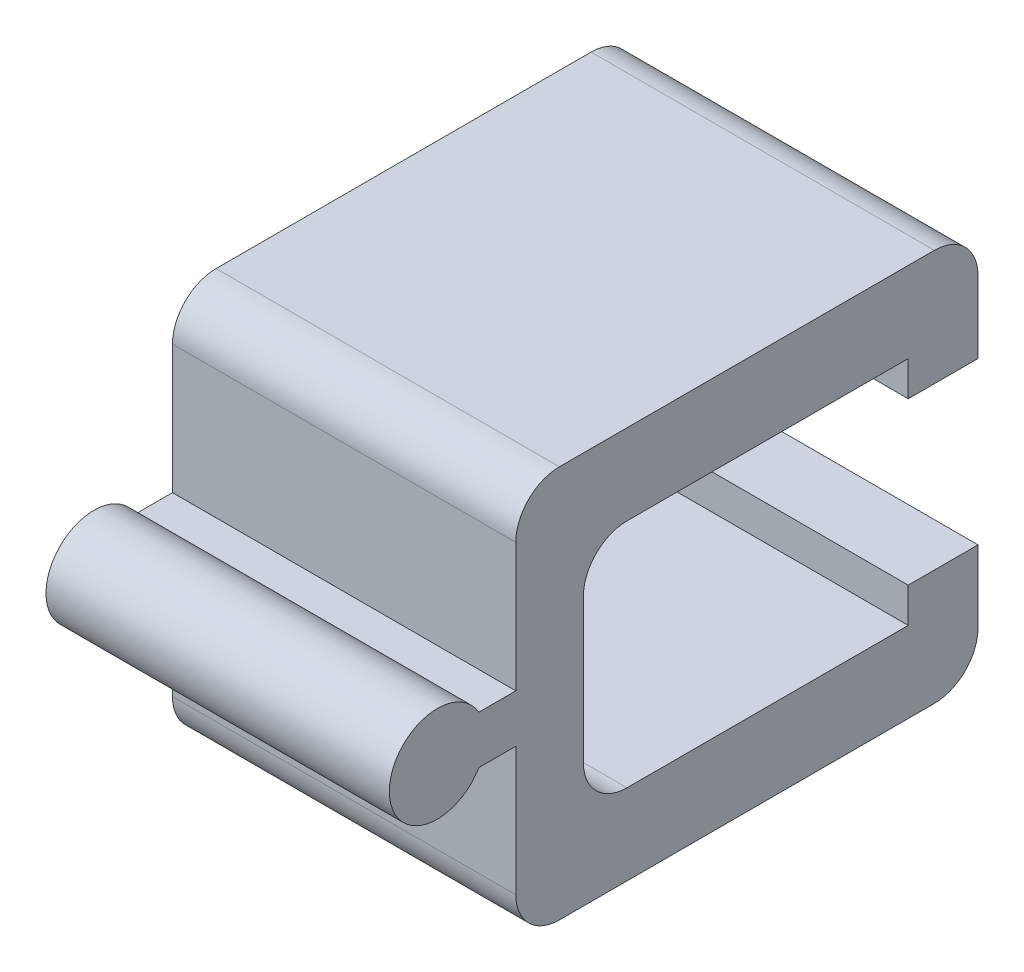
SolidWorks part; units mm, degrees
ref_plane "Front Plane" through (0, 0, 0) normal (0, 0, 1) x (1, 0, 0)
ref_plane "Top Plane" through (0, 0, 0) normal (0, 1, 0) x (1, 0, 0)
ref_plane "Right Plane" through (0, 0, 0) normal (1, 0, 0) x (0, 0, -1)
sketch "Sketch1" plane through (0, 0, 0) normal (1, 0, 0) x (0, 0, -1)
  line L5 (106.9183, 0.6042) -> (93.4563, 0.6042)
  line L11 (104.8863, -7.4603) -> (104.8863, -8.4763)
  line L15 (106.9183, 0.6042) -> (106.9183, -2.7613)
  line L16 (106.9183, -2.7613) -> (104.8863, -2.7613)
  line L17 (104.8863, -2.7613) -> (104.8863, -1.7453)
  line L18 (104.8863, -1.7453) -> (95.4248, -1.7453)
  line L19 (95.4248, -1.7453) -> (95.4248, -8.4763)
  line L20 (93.4563, 0.6042) -> (93.4563, -10.8258)
  line L21 (104.8863, -8.4763) -> (95.4248, -8.4763)
  line L23 (106.9183, -7.4603) -> (104.8863, -7.4603)
  line L25 (106.9183, -10.8258) -> (93.4563, -10.8258)
  line L26 (106.9183, -7.4603) -> (106.9183, -10.8258)
  point P16 (93.4563, -5.1108)
  point P17 (95.4248, -5.1108)
  dimension "D1" = 9.4615
  dimension "D2" = 6.731
  dimension "D3" = 1.016
  dimension "D4" = 2.032
  dimension "D5" = 13.462
  dimension "D6" = 11.43
  dimension "D7" = 1.016
  dimension "D8" = 13.462
extrude "MainBody" add sketch "Sketch1" along normal mid plane 10
sketch "Sketch4" plane through (0, -10.8258, 0) normal (0, -1, 0) x (1, 0, 0)
  line L4 (-5, -93.4563) -> (-5, -106.9183)
  line L5 (-5, -106.9183) -> (5, -106.9183)
  line L6 (5, -106.9183) -> (5, -93.4563)
  line L7 (5, -93.4563) -> (-5, -93.4563)
  line L8 (-5, -93.4563) -> (-5, -106.9183)
  line L9 (-5, -106.9183) -> (5, -106.9183)
  line L10 (5, -106.9183) -> (5, -93.4563)
  line L11 (5, -93.4563) -> (-5, -93.4563)
  dimension "D1" = 0
extrude "Boss-Extrude1" [suppressed] add sketch "Sketch4" along normal blind 6
hole_wizard "#6-32 Tapped Hole1" [suppressed] positions "Sketch2" profile "Sketch3" tap size "#6-32" standard "ANSI Inch"
sketch "Sketch2" [suppressed] plane through (0, 0, 6.0052) normal (0, 0, 1) x (1, 0, 0)
  line L2 (5, -14.1012) -> (-5, -14.1012) construction
  point P0 (0, -11.1012)
  point P12 (0, -14.1012)
  dimension "D1" = 3
sketch "Sketch3" plane through (0, -11.1012, 6.0052) normal (1, 0, 0) x (0, -1, 0)
  line L0 (0, 0) -> (0, 15.5)
  line L1 (0, 15.5) -> (1.7526, 15.5)
  line L2 (1.7526, 15.5) -> (1.7526, 0)
  line L5 (1.7526, 0) -> (0, 0)
  line L11 (0, -6.35) -> (0, 107.95) construction
  dimension "Thread Major Dia." = 3.5052
  dimension "Thru Tap Drill Depth" = 15.5
sketch "Sketch5" plane through (0, 0, -93.4563) normal (0, 0, 1) x (1, 0, 0)
  line L0 (5, 0.6042) -> (5, -10.8258) construction
  line L1 (-5, -10.8258) -> (5, -10.8258)
  line L2 (-5, -10.8258) -> (-5, 69.1742)
  line L3 (-5, 69.1742) -> (5, 69.1742)
  line L4 (5, -10.8258) -> (5, 69.1742)
  dimension "D1" = 80
extrude "HeightSupport" [suppressed] add sketch "Sketch5" along normal blind 4
fillet "Fillet2" [suppressed] radius 2
sketch "Sketch6" plane through (-5, 0, 0) normal (-1, 0, 0) x (0, 0, 1)
  line L0 (-93.5416, 72.7238) -> (-93.5416, 69.5488)
  line L2 (-93.5416, 69.3588) -> (-91.2556, 69.3588)
  line L6 (-93.5416, 67.8602) -> (-93.5416, 69.3588)
  line L7 (-93.5416, 69.3588) -> (-93.5416, 67.8602)
  line L8 (-93.5416, 67.8602) -> (-91.2556, 67.8602)
  line L9 (-91.2556, 69.3588) -> (-91.2556, 67.8602)
  line L14 (-106.9183, -2.7613) -> (-104.8863, -2.7613)
  line L15 (-104.8863, -2.7613) -> (-104.8863, -1.7453)
  line L16 (-104.8863, -1.7453) -> (-95.4248, -1.7453)
  line L17 (-95.4248, -1.7453) -> (-95.4248, -8.4763)
  line L18 (-95.4248, -8.4763) -> (-104.8863, -8.4763)
  line L19 (-104.8863, -8.4763) -> (-104.8863, -7.4603)
  line L20 (-104.8863, -7.4603) -> (-106.9183, -7.4603)
  line L21 (-106.9183, -7.4603) -> (-106.9183, -10.8258)
  line L22 (-106.9183, -10.8258) -> (-93.4563, -10.8258)
  line L23 (-93.4563, -10.8258) -> (-93.4563, 0.6042)
  line L26 (-93.4563, 0.6042) -> (-106.9183, 0.6042)
  line L27 (-106.9183, 0.6042) -> (-106.9183, -2.7613)
  line L28 (-106.9183, -2.7613) -> (-104.8863, -2.7613)
  line L29 (-104.8863, -2.7613) -> (-104.8863, -1.7453)
  line L30 (-104.8863, -1.7453) -> (-95.4248, -1.7453)
  line L31 (-95.4248, -1.7453) -> (-95.4248, -8.4763)
  line L32 (-95.4248, -8.4763) -> (-104.8863, -8.4763)
  line L34 (-104.8863, -7.4603) -> (-106.9183, -7.4603)
  line L35 (-106.9183, -7.4603) -> (-106.9183, -10.8258)
  line L36 (-106.9183, -10.8258) -> (-93.4563, -10.8258)
  line L40 (-93.4563, 0.6042) -> (-106.9183, 0.6042)
  line L41 (-106.9183, 0.6042) -> (-106.9183, -2.7613)
  line L48 (-104.8863, -8.4763) -> (-104.8863, -7.4603)
  line L49 (-93.4563, -10.8258) -> (-93.4563, 0.6042)
  circle A3 centre (-91.2556, 68.6095) radius 1.3843
  point P10 (-64.013, 68.7238)
  dimension "D5" = 2.7686
  dimension "D2" = 3.175
  dimension "D3" = 1.4986
  dimension "D4" = 2.286
  dimension "D1" = 0
extrude "Cut-Extrude1" [suppressed] cut sketch "Sketch6" against normal up to surface (10 mm away)
pattern_linear "LPattern1" [suppressed] count 10 spacing 6.35
sketch "Sketch7" [suppressed] plane through (0, 0, -89.5417) normal (0, 0, 1) x (1, 0, 0)
  line L4 (-5, 73.9476) -> (-5, -6.0524)
  line L5 (-5, -6.0524) -> (5, -6.0524)
  line L6 (5, -6.0524) -> (5, 73.9476)
  line L7 (5, 73.9476) -> (-5, 73.9476)
  line L8 (-5, 73.9476) -> (-5, -6.0524)
  line L10 (5, -6.0524) -> (5, 73.9476)
  line L11 (5, 73.9476) -> (-5, 73.9476)
  line L13 (-5, -6.0524) -> (5, -6.0524)
  dimension "D1" = 0
extrude "Boss-Extrude2" [suppressed] add sketch "Sketch7" along normal blind 1.27
sketch "Sketch8" [suppressed] plane through (0, -8.1012, 0) normal (0, -1, 0) x (1, 0, 0)
  line L4 (-5, -88.1629) -> (-5, -108.4329)
  line L5 (-5, -108.4329) -> (5, -108.4329)
  line L6 (5, -108.4329) -> (5, -88.1629)
  line L7 (5, -88.1629) -> (-5, -88.1629)
  line L8 (-5, -88.1629) -> (-5, -108.4329)
  line L9 (-5, -108.4329) -> (5, -108.4329)
  line L10 (5, -108.4329) -> (5, -88.1629)
  line L11 (5, -88.1629) -> (-5, -88.1629)
  dimension "D1" = 0
extrude "Cut-Extrude2" [suppressed] cut sketch "Sketch8" against normal offset from surface (73.65 mm away) 2.54
sketch "Sketch9" [suppressed] plane through (0, 0, -88.2717) normal (0, 0, 1) x (1, 0, 0)
  line L4 (5, 73.9476) -> (-5, 73.9476)
  line L5 (-5, 73.9476) -> (-5, -6.0524)
  line L6 (-5, -6.0524) -> (5, -6.0524)
  line L7 (5, -6.0524) -> (5, 73.9476)
  line L8 (5, 73.9476) -> (-5, 73.9476)
  line L9 (-5, 73.9476) -> (-5, -6.0524)
  line L10 (-5, -6.0524) -> (5, -6.0524)
  line L11 (5, -6.0524) -> (5, 73.9476)
  dimension "D1" = 0
extrude "Boss-Extrude3" [suppressed] add sketch "Sketch9" along normal blind 3.175
sketch "Sketch10" plane through (5, 0, 0) normal (1, 0, 0) x (0, 0, -1)
  line L0 (91.1703, -5.1108) -> (93.4563, -5.1108)
  line L1 (93.4563, 0.6042) -> (93.4563, -10.8258)
  line L2 (106.9183, 0.6042) -> (93.4563, 0.6042) construction
  line L3 (93.4563, -4.4123) -> (91.1703, -4.4123)
  line L4 (93.4563, -4.4123) -> (93.4563, -5.8093)
  line L5 (93.4563, -5.8093) -> (91.1703, -5.8093)
  line L6 (91.1703, -4.4123) -> (91.1703, -5.8093)
  circle A0 centre (91.1703, -5.1108) radius 1.397
  line M6 (93.4563, 0.6042) -> (93.4563, -10.8258)
  dimension "D4" = 2.794
  dimension "D1" = 1.397
  dimension "D2" = 2.286
  dimension "D3" = 5.715
extrude "Boss-Extrude4" add sketch "Sketch10" against normal up to surface (10 mm away) contours L3 A0 L5 L6 | L0 A0 L3 L6 | L5 A0 L0 L6 | A0 L0 L1 L3 | A0 L5 L0 M6 up to face at (-5, -5.1108, -102.0817)
fillet "Fillet4" radius 1.27 6 edges at (0, -10.8258, -106.9183) (0, -10.8258, -93.4563) (0, -8.4763, -95.4248) (0, -1.7453, -95.4248) (0, 0.6042, -93.4563) (0, 0.6042, -106.9183)
equation "\"HeightBarThickness\"= 1.5875"
equation "\"HeightBarWidth\"=6"
equation "\"SheetThickness\"= 1.5875"
equation "\"HeightBarTolerance\"= 0.1mm"
equation "\"HeightBarHeight\"= 80mm"
equation "\"D1@Sketch5\"=\"HeightBarHeight\""
equation "\"HoleDiameter\"=3.2"
equation "\"OpeningSlotWidth\"=3"
equation "\"Joint Tolerance\"= .009in"
equation "\"Joint Thickness\"= .05in"
equation "\"Joint Radius\"= .05in"
equation "\"D5@Sketch6\"=(\"Joint Radius\" * 2) + \"Joint Tolerance\""
equation "\"Joint Height\"= .09in"
equation "\"D3@Sketch6\"=\"Joint Thickness\" + \"Joint Tolerance\""
